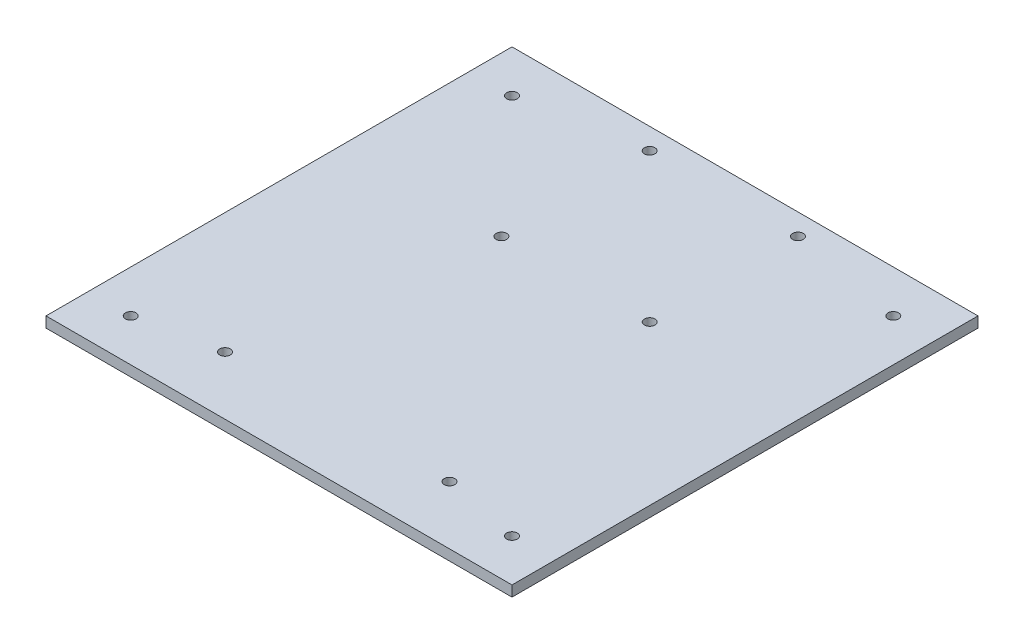
SolidWorks part; units mm, degrees
ref_plane "Alzado" through (0, 0, 0) normal (0, 0, 1) x (1, 0, 0)
ref_plane "Planta" through (0, 0, 0) normal (0, 1, 0) x (1, 0, 0)
ref_plane "Vista lateral" through (0, 0, 0) normal (1, 0, 0) x (0, 0, -1)
sketch "Croquis1" plane through (0, 0, 0) normal (0, 1, 0) x (1, 0, 0)
  line L1 (110, -110) -> (-110, -110)
  line L2 (110, -110) -> (110, 110)
  line L3 (110, 110) -> (-110, 110)
  line L4 (-110, -110) -> (-110, 110)
  line L5 (110, -110) -> (-110, 110) construction
  line L6 (110, 110) -> (-110, -110) construction
  point P0 (0, 0)
  dimension "D1" = 220
  dimension "D2" = 220
extrude "Saliente-Extruir1" add sketch "Croquis1" along normal blind 5
sketch "Croquis2" plane through (0, 5, 0) normal (0, 1, 0) x (1, 0, 0)
  line L0 (0, 256.8961) -> (0, -255.1691) construction
  line L1 (242.6481, 0) -> (-300.5037, 0) construction
  line L2 (110, 110) -> (-110, 110) construction
  circle A0 centre (-90, 90) radius 2.5
  circle A1 centre (90, 90) radius 2.5
  circle A2 centre (90, -90) radius 2.5
  circle A3 centre (-90, -90) radius 2.5
  dimension "D1" = 90
  dimension "D4" = 5
  dimension "D2" = 110
  dimension "D3" = 90
extrude "Cortar-Extruir1" cut sketch "Croquis2" against normal through all
sketch "Croquis3" plane through (0, 5, 0) normal (0, 1, 0) x (1, 0, 0)
  line L0 (-110, 110) -> (-110, -110) construction
  line L1 (110, -110) -> (110, 110) construction
  line L2 (110, 110) -> (-110, 110) construction
  line L3 (-110, -110) -> (110, -110) construction
  circle A0 centre (-35, 100) radius 2.5
  circle A1 centre (35, 100) radius 2.5
  circle A2 centre (-35, 30) radius 2.5
  circle A3 centre (35, 30) radius 2.5
  circle A4 centre (-53, -82.5) radius 2.5
  circle A5 centre (53, -82.5) radius 2.5
  dimension "D3" = 5
  dimension "D4" = 5
  dimension "D5" = 10
  dimension "D7" = 5
  dimension "D8" = 5
  dimension "D9" = 80
  dimension "D10" = 80
  dimension "D13" = 57
  dimension "D14" = 5
  dimension "D15" = 27.5
  dimension "D16" = 27.5
  dimension "D17" = 5
  dimension "D18" = 57
  dimension "D1" = 75
  dimension "D2" = 75
  dimension "D6" = 10
  dimension "D11" = 75
  dimension "D12" = 75
extrude "Cortar-Extruir2" cut sketch "Croquis3" against normal blind 10
